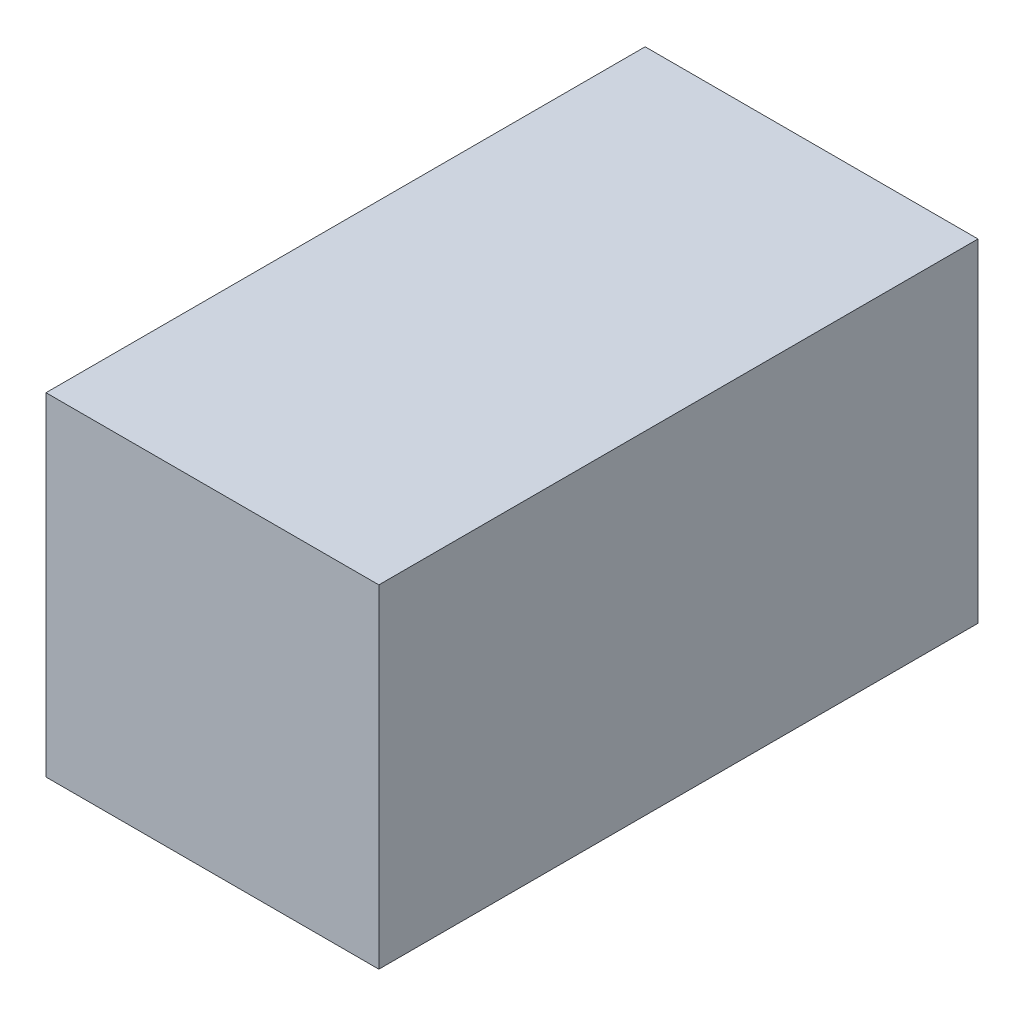
SolidWorks part; units mm, degrees
material "Acciaio al carbonio semplice"
ref_plane "Piano frontale" through (0, 0, 0) normal (0, 0, 1) x (1, 0, 0)
ref_plane "Piano superiore" through (0, 0, 0) normal (0, 1, 0) x (1, 0, 0)
ref_plane "Piano destro" through (0, 0, 0) normal (1, 0, 0) x (0, 0, -1)
sketch "Schizzo1" plane through (0, 0, 0) normal (0, 0, -1) x (-1, 0, 0)
  line L1 (200, -200) -> (-200, -200)
  line L2 (200, -200) -> (200, 200)
  line L3 (200, 200) -> (-200, 200)
  line L4 (-200, -200) -> (-200, 200)
  line L5 (200, -200) -> (-200, 200) construction
  line L6 (200, 200) -> (-200, -200) construction
  point P0 (0, 0)
  dimension "D1" = 400
  dimension "D2" = 400
extrude "Estrusione-Estrusione1" add sketch "Schizzo1" against normal blind 720
